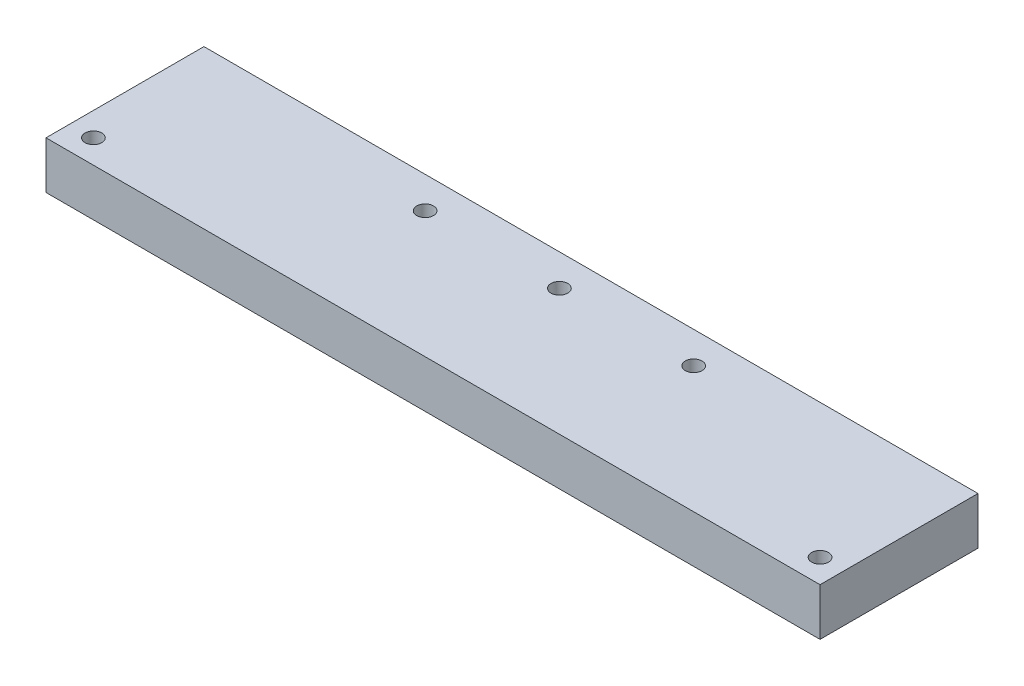
SolidWorks part; units mm, degrees
ref_plane "Front" through (0, 0, 0) normal (0, 0, 1) x (1, 0, 0)
ref_plane "Top" through (0, 0, 0) normal (0, 1, 0) x (1, 0, 0)
ref_plane "Right" through (0, 0, 0) normal (1, 0, 0) x (0, 0, -1)
sketch "Sketch1" plane through (0, 0, 0) normal (0, 1, 0) x (1, 0, 0)
  line L1 (-155.575, -31.75) -> (155.575, -31.75)
  line L2 (-155.575, -31.75) -> (-155.575, 31.75)
  line L3 (-155.575, 31.75) -> (155.575, 31.75)
  line L4 (155.575, -31.75) -> (155.575, 31.75)
  line L5 (-155.575, -31.75) -> (155.575, 31.75) construction
  line L6 (-155.575, 31.75) -> (155.575, -31.75) construction
  point P0 (0, 0)
  point P6 (0, 0)
  dimension "D1" = 311.15
  dimension "D2" = 63.5
extrude "Boss-Extrude1" add sketch "Sketch1" along normal mid plane 19.05 contours L3 L4 L1 L2
sketch "Sketch2" plane through (0, 9.525, 0) normal (0, 1, 0) x (1, 0, 0)
  line L0 (0, -50) -> (0, 50) construction
  line L1 (-53.975, 19.05) -> (53.975, 19.05) construction
  line L2 (155.575, -31.75) -> (155.575, 31.75) construction
  line L3 (-155.575, -31.75) -> (-155.575, 31.75) construction
  line L4 (-155.575, -31.75) -> (155.575, -31.75) construction
  line L5 (-155.575, 31.75) -> (155.575, 31.75) construction
  point P0 (-53.975, 19.05)
  point P1 (0, 19.05)
  point P2 (53.975, 19.05)
  point P5 (-146.05, -22.225)
  point P6 (146.05, -22.225)
  point P7 (0, 19.05)
  point P18 (0, 0)
  dimension "D1" = 101.6
  dimension "D2" = 9.525
  dimension "D3" = 9.525
  dimension "D4" = 12.7
  dimension "D5" = 9.525
hole_wizard "1/4 Clearance Hole1" positions "Sketch3" profile "Sketch4" hole size "1/4" standard "ANSI Inch"
sketch "Sketch3" plane through (0, 9.525, 0) normal (0, 1, 0) x (1, 0, 0)
  point P0 (-53.975, 19.05)
  point P3 (0, 19.05)
  point P6 (53.975, 19.05)
  point P9 (146.05, -22.225)
  point P12 (-146.05, -22.225)
sketch "Sketch4" plane through (-53.975, 9.525, -19.05) normal (1, 0, 0) x (0, 0, 1)
  line L0 (0, 0) -> (0, 18.5398)
  line L1 (0, 18.5398) -> (3.3782, 16.51)
  line L2 (3.3782, 16.51) -> (3.3782, 0)
  line L5 (3.3782, 0) -> (0, 0)
  line L10 (0, 18.5398) -> (-3.3782, 16.51) construction
  line L11 (0, -6.35) -> (0, 107.95) construction
  dimension "Hole Dia." = 6.7564
  dimension "Hole Depth" = 16.51
  dimension "Drill Angle" = 118
